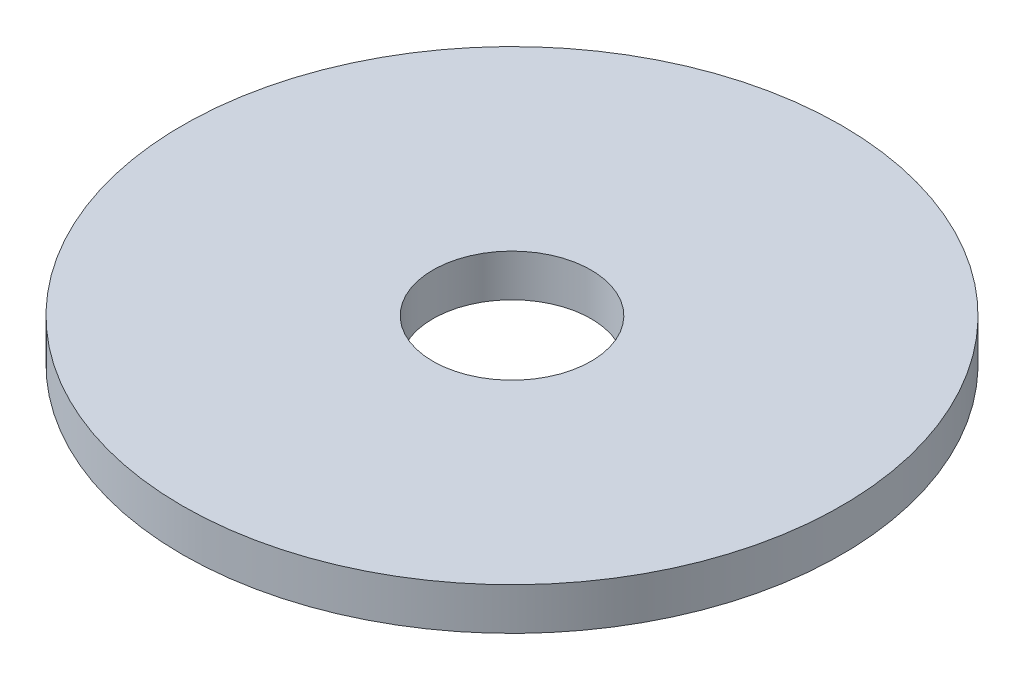
SolidWorks part; units mm, degrees
material "Stainless Steel (ferritic)"
ref_plane "Front Plane" through (0, 0, 0) normal (0, 0, 1) x (1, 0, 0)
ref_plane "Top Plane" through (0, 0, 0) normal (0, 1, 0) x (1, 0, 0)
ref_plane "Right Plane" through (0, 0, 0) normal (1, 0, 0) x (0, 0, -1)
sketch "Sketch1" plane through (0, 0, 0) normal (0, 1, 0) x (1, 0, 0)
  circle A0 centre (0, 0) radius 3
  circle A1 centre (0, 0) radius 12.5
  dimension "D1" = 25
  dimension "D2" = 6
extrude "Boss-Extrude1" add sketch "Sketch1" along normal blind 1.6
